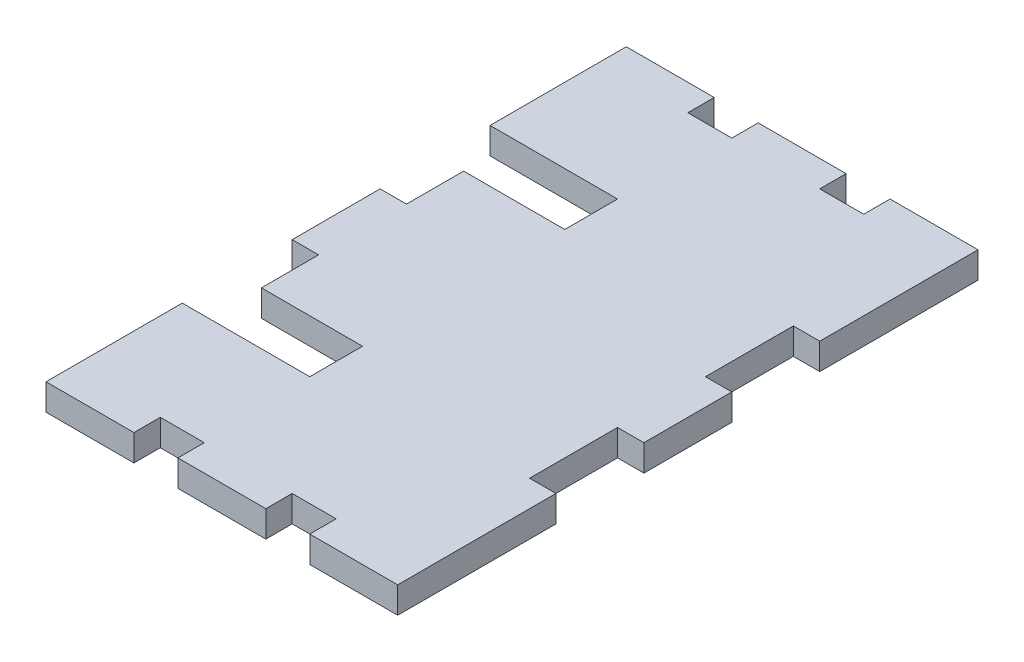
SolidWorks part; units mm, degrees
ref_plane "Plano frontal" through (0, 0, 0) normal (0, 0, 1) x (1, 0, 0)
ref_plane "Plano superior" through (0, 0, 0) normal (0, 1, 0) x (1, 0, 0)
ref_plane "Plano direito" through (0, 0, 0) normal (1, 0, 0) x (0, 0, -1)
sketch "Esboço1" plane through (0, 0, 0) normal (0, 1, 0) x (1, 0, 0)
  line L4 (-40, 0) -> (-60, 0)
  line L6 (-60, -36) -> (-54, -36)
  line L7 (-54, -36) -> (-54, -56)
  line L8 (-54, -56) -> (-60, -56)
  line L10 (-60, -76) -> (-54, -76)
  line L11 (-54, -76) -> (-54, -96)
  line L12 (-54, -96) -> (-60, -96)
  line L14 (-60, -132) -> (-40, -132)
  line L18 (-30, -132) -> (-10, -132)
  line L22 (0, -132) -> (20, -132)
  line L24 (20, -96) -> (14, -96)
  line L25 (14, -96) -> (14, -76)
  line L26 (14, -76) -> (20, -76)
  line L28 (20, -56) -> (14, -56)
  line L29 (14, -56) -> (14, -36)
  line L30 (14, -36) -> (20, -36)
  line L36 (20, 0) -> (20, -36)
  line L38 (20, -96) -> (20, -132)
  line L39 (-60, -132) -> (-60, -96)
  line L40 (-60, -76) -> (-60, -56)
  line L41 (-60, -36) -> (-60, 0)
  line L43 (-30, 0) -> (-10, 0)
  line L44 (0, 0) -> (20, 0)
  line L45 (-40, 0) -> (-40, -6)
  line L46 (-40, -6) -> (-30, -6)
  line L47 (-30, -6) -> (-30, 0)
  line L48 (-10, 0) -> (-10, -6)
  line L49 (-10, -6) -> (0, -6)
  line L50 (0, -6) -> (0, 0)
  line L51 (-40, -132) -> (-40, -126)
  line L52 (-40, -126) -> (-30, -126)
  line L53 (-30, -126) -> (-30, -132)
  line L54 (-10, -132) -> (-10, -126)
  line L55 (-10, -126) -> (0, -126)
  line L56 (0, -126) -> (0, -132)
  line L57 (20, -56) -> (20, -76)
  line L58 (-60, -66) -> (-31, -66)
  line L59 (-31, -43) -> (-31, -89)
  line L60 (-31, -101) -> (-60, -101)
  line L62 (-31, -43) -> (-31, -31)
  line L66 (-31, -89) -> (-31, -101)
  line L69 (-31, -89) -> (-54, -89)
  line L70 (-31, -43) -> (-54, -43)
  line L71 (-31, -31) -> (-60, -31)
  line L72 (-60, -31) -> (-60, -36)
  line L73 (-54, -36) -> (-54, -43)
  line L74 (-60, -101) -> (-60, -96)
  line L75 (-54, -96) -> (-54, -89)
  dimension "D2" = 6
  dimension "D3" = 6
  dimension "D4" = 80
  dimension "D5" = 20
  dimension "D6" = 20
  dimension "D7" = 20
  dimension "D8" = 6
  dimension "D9" = 20
  dimension "D10" = 10
  dimension "D11" = 10
  dimension "D12" = 6
  dimension "D13" = 36
  dimension "D18" = 29
extrude "Ressalto-extrusão9" add sketch "Esboço1" along normal blind 6 contours L71 L62 L59 L66 L60 L39 L14 L51 L52 L53 L18 L54 L55 L56 L22 L38 L24 L25 L26 L57 L28 L29 L30 L36 L44 L50 L49 L48 L43 L47 L46 L45 L4 L41 | L59 L70 L7 L8 L40 L58 | L69 L59 L58 L40 L10 L11
